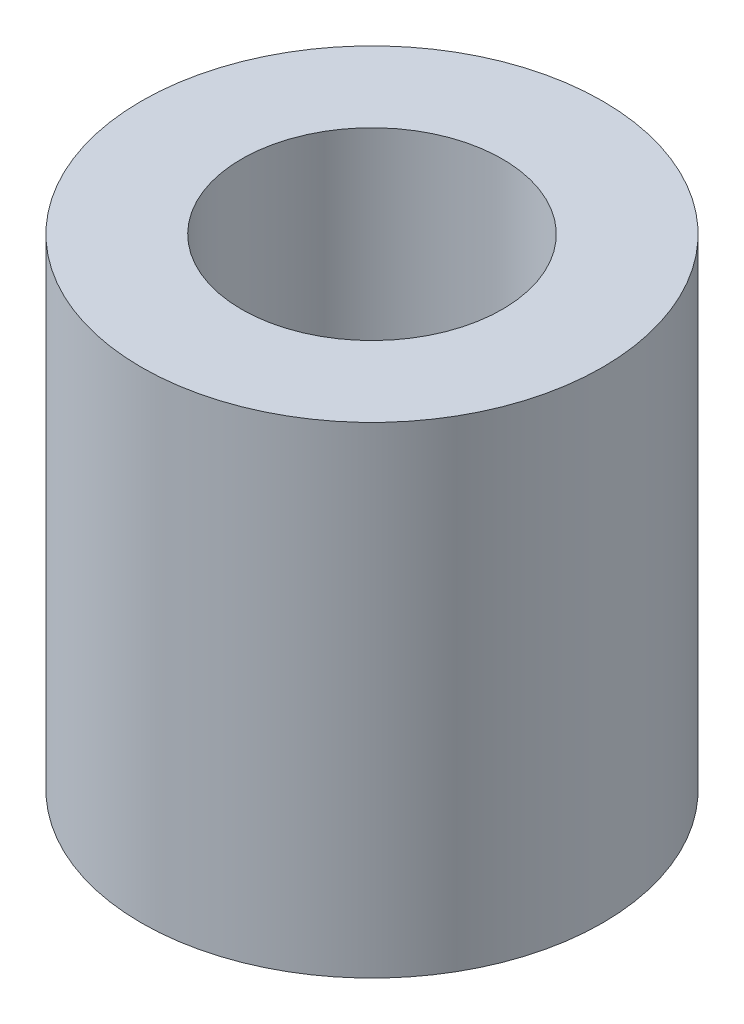
SolidWorks part; units mm, degrees
ref_plane "Front Plane" through (0, 0, 0) normal (0, 0, 1) x (1, 0, 0)
ref_plane "Top Plane" through (0, 0, 0) normal (0, 1, 0) x (1, 0, 0)
ref_plane "Right Plane" through (0, 0, 0) normal (1, 0, 0) x (0, 0, -1)
sketch "Sketch1" plane through (0, 0, 0) normal (0, 1, 0) x (1, 0, 0)
  circle A0 centre (0, 0) radius 3.25
  circle A1 centre (0, 0) radius 5.75
  dimension "D1" = 6.5
  dimension "D2" = 2.5
extrude "Body" add sketch "Sketch1" along normal blind 12
